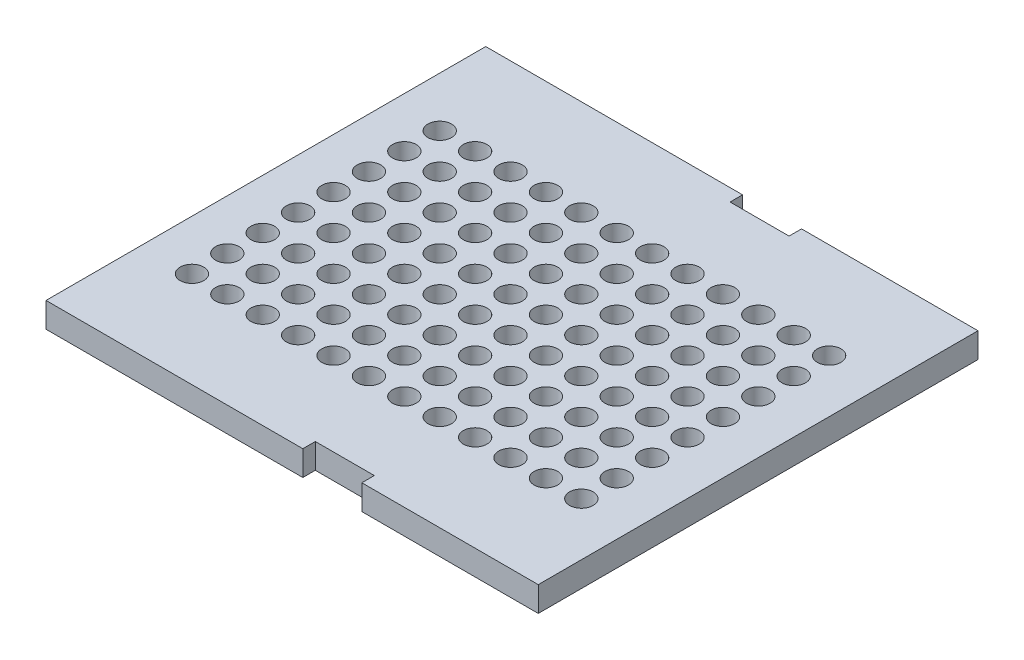
SolidWorks part; units mm, degrees
ref_plane "Front Plane" through (0, 0, 0) normal (0, 0, 1) x (1, 0, 0)
ref_plane "Top Plane" through (0, 0, 0) normal (0, 1, 0) x (1, 0, 0)
ref_plane "Right Plane" through (0, 0, 0) normal (1, 0, 0) x (0, 0, -1)
sketch "Sketch1" plane through (0, 0, 0) normal (0, 1, 0) x (1, 0, 0)
  line L0 (-69.2968, 161.778) -> (55.6973, 161.778)
  line L1 (3.3404, 49.978) -> (51.1304, 49.978)
  line L7 (51.1304, 49.978) -> (55.6973, 49.978)
  line L8 (55.6973, 161.778) -> (55.6973, 49.978)
  line L9 (-69.2968, 161.778) -> (-69.4527, 161.778)
  line L11 (3.3404, 49.978) -> (-69.4527, 49.978)
  line L12 (-69.4527, 161.778) -> (-69.4527, 49.978)
  line L13 (-56.7527, 105.878) -> (42.2473, 105.878) construction
  line L14 (-56.7527, 137.378) -> (42.2473, 137.378) construction
  line L15 (-56.7527, 137.378) -> (-56.7527, 74.378) construction
  line L16 (-56.7527, 74.378) -> (42.2473, 74.378) construction
  line L17 (42.2473, 137.378) -> (42.2473, 74.378) construction
  circle A0 centre (-56.7527, 137.378) radius 3
  circle A1 centre (-47.7527, 137.378) radius 3
  circle A2 centre (-38.7527, 137.378) radius 3
  circle A3 centre (-29.7527, 137.378) radius 3
  circle A4 centre (-20.7527, 137.378) radius 3
  circle A5 centre (-11.7527, 137.378) radius 3
  circle A6 centre (-2.7527, 137.378) radius 3
  circle A7 centre (6.2473, 137.378) radius 3
  circle A8 centre (15.2473, 137.378) radius 3
  circle A9 centre (24.2473, 137.378) radius 3
  circle A10 centre (33.2473, 137.378) radius 3
  circle A11 centre (42.2473, 137.378) radius 3
  circle A12 centre (-47.7527, 128.378) radius 3
  circle A13 centre (-38.7527, 128.378) radius 3
  circle A14 centre (-29.7527, 128.378) radius 3
  circle A15 centre (-20.7527, 128.378) radius 3
  circle A16 centre (-11.7527, 128.378) radius 3
  circle A17 centre (-2.7527, 128.378) radius 3
  circle A18 centre (6.2473, 128.378) radius 3
  circle A19 centre (15.2473, 128.378) radius 3
  circle A20 centre (24.2473, 128.378) radius 3
  circle A21 centre (33.2473, 128.378) radius 3
  circle A22 centre (42.2473, 128.378) radius 3
  circle A23 centre (-47.7527, 119.378) radius 3
  circle A24 centre (-38.7527, 119.378) radius 3
  circle A25 centre (-29.7527, 119.378) radius 3
  circle A26 centre (-20.7527, 119.378) radius 3
  circle A27 centre (-11.7527, 119.378) radius 3
  circle A28 centre (-2.7527, 119.378) radius 3
  circle A29 centre (6.2473, 119.378) radius 3
  circle A30 centre (15.2473, 119.378) radius 3
  circle A31 centre (24.2473, 119.378) radius 3
  circle A32 centre (33.2473, 119.378) radius 3
  circle A33 centre (42.2473, 119.378) radius 3
  circle A34 centre (-47.7527, 110.378) radius 3
  circle A35 centre (-38.7527, 110.378) radius 3
  circle A36 centre (-29.7527, 110.378) radius 3
  circle A37 centre (-20.7527, 110.378) radius 3
  circle A38 centre (-11.7527, 110.378) radius 3
  circle A39 centre (-2.7527, 110.378) radius 3
  circle A40 centre (6.2473, 110.378) radius 3
  circle A41 centre (15.2473, 110.378) radius 3
  circle A42 centre (24.2473, 110.378) radius 3
  circle A43 centre (33.2473, 110.378) radius 3
  circle A44 centre (42.2473, 110.378) radius 3
  circle A45 centre (-47.7527, 101.378) radius 3
  circle A46 centre (-38.7527, 101.378) radius 3
  circle A47 centre (-29.7527, 101.378) radius 3
  circle A48 centre (-20.7527, 101.378) radius 3
  circle A49 centre (-11.7527, 101.378) radius 3
  circle A50 centre (-2.7527, 101.378) radius 3
  circle A51 centre (6.2473, 101.378) radius 3
  circle A52 centre (15.2473, 101.378) radius 3
  circle A53 centre (24.2473, 101.378) radius 3
  circle A54 centre (33.2473, 101.378) radius 3
  circle A55 centre (42.2473, 101.378) radius 3
  circle A56 centre (-47.7527, 92.378) radius 3
  circle A57 centre (-38.7527, 92.378) radius 3
  circle A58 centre (-29.7527, 92.378) radius 3
  circle A59 centre (-20.7527, 92.378) radius 3
  circle A60 centre (-11.7527, 92.378) radius 3
  circle A61 centre (-2.7527, 92.378) radius 3
  circle A62 centre (6.2473, 92.378) radius 3
  circle A63 centre (15.2473, 92.378) radius 3
  circle A64 centre (24.2473, 92.378) radius 3
  circle A65 centre (33.2473, 92.378) radius 3
  circle A66 centre (42.2473, 92.378) radius 3
  circle A67 centre (-47.7527, 83.378) radius 3
  circle A68 centre (-38.7527, 83.378) radius 3
  circle A69 centre (-29.7527, 83.378) radius 3
  circle A70 centre (-20.7527, 83.378) radius 3
  circle A71 centre (-11.7527, 83.378) radius 3
  circle A72 centre (-2.7527, 83.378) radius 3
  circle A73 centre (6.2473, 83.378) radius 3
  circle A74 centre (15.2473, 83.378) radius 3
  circle A75 centre (24.2473, 83.378) radius 3
  circle A76 centre (33.2473, 83.378) radius 3
  circle A77 centre (42.2473, 83.378) radius 3
  circle A78 centre (-47.7527, 74.378) radius 3
  circle A79 centre (-38.7527, 74.378) radius 3
  circle A80 centre (-29.7527, 74.378) radius 3
  circle A81 centre (-20.7527, 74.378) radius 3
  circle A82 centre (-11.7527, 74.378) radius 3
  circle A83 centre (-2.7527, 74.378) radius 3
  circle A84 centre (6.2473, 74.378) radius 3
  circle A85 centre (15.2473, 74.378) radius 3
  circle A86 centre (24.2473, 74.378) radius 3
  circle A87 centre (33.2473, 74.378) radius 3
  circle A88 centre (42.2473, 74.378) radius 3
  circle A89 centre (-56.7527, 128.378) radius 3
  circle A90 centre (-56.7527, 119.378) radius 3
  circle A91 centre (-56.7527, 110.378) radius 3
  circle A92 centre (-56.7527, 101.378) radius 3
  circle A93 centre (-56.7527, 92.378) radius 3
  circle A94 centre (-56.7527, 83.378) radius 3
  circle A95 centre (-56.7527, 74.378) radius 3
  point P201 (0, 0)
  dimension "D3" = 6
  dimension "D1" = 111.8
  dimension "D2" = 125.15
  dimension "D6" = 55.9
  dimension "D7" = 12.7
  dimension "D8" = 60.0931
  dimension "D9" = 9
  dimension "D10" = 9
  dimension "D4" = 12
  dimension "D5" = 8
extrude "Boss-Extrude1" add sketch "Sketch1" along normal blind 6.35
sketch "Sketch4" plane through (0, 0, 0) normal (0, -1, 0) x (1, 0, 0)
  line L0 (3.3404, -49.978) -> (51.1304, -49.978) construction
  line L1 (-4.1596, -49.978) -> (10.8404, -49.978)
  line L3 (-4.1596, -49.978) -> (-4.1596, -53.153)
  line L4 (-4.1596, -53.153) -> (10.8404, -53.153)
  line L5 (10.8404, -49.978) -> (10.8404, -53.153)
  line L6 (-56.7527, -105.878) -> (42.2473, -105.878) construction
  line L7 (-4.1596, -158.603) -> (10.8404, -158.603)
  line L8 (10.8404, -161.778) -> (10.8404, -158.603)
  line L9 (-4.1596, -161.778) -> (10.8404, -161.778)
  line L10 (-4.1596, -161.778) -> (-4.1596, -158.603)
  point P4 (3.3404, -53.153)
  dimension "D1" = 15
  dimension "D2" = 3.175
extrude "Cut-Extrude1" cut sketch "Sketch4" against normal through all
equation "\"D6@Sketch1\"=\"D1@Sketch1\"/2"
